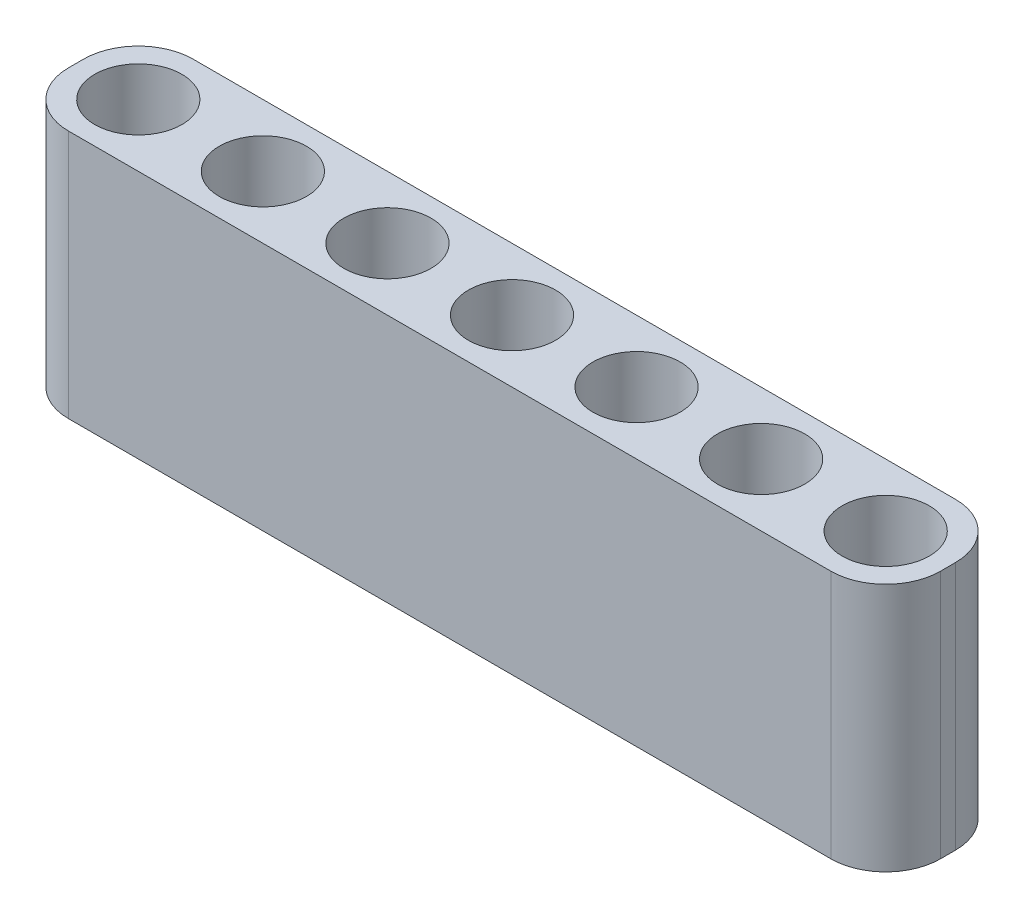
SolidWorks part; units mm, degrees
ref_plane "Front Plane" through (0, 0, 0) normal (0, 0, 1) x (1, 0, 0)
ref_plane "Top Plane" through (0, 0, 0) normal (0, 1, 0) x (1, 0, 0)
ref_plane "Right Plane" through (0, 0, 0) normal (1, 0, 0) x (0, 0, -1)
sketch "Sketch1" plane through (0, 0, 0) normal (0, 1, 0) x (1, 0, 0)
  line L1 (2.2, 0) -> (32.8, 0)
  line L2 (0, 2.2) -> (0, 2.8)
  line L3 (2.2, 5) -> (32.8, 5)
  line L4 (35, 2.2) -> (35, 2.8)
  circle A0 centre (2.5, 2.5) radius 1.75
  circle A2 centre (7.5, 2.5) radius 1.75
  circle A3 centre (12.5, 2.5) radius 1.75
  circle A4 centre (17.5, 2.5) radius 1.75
  circle A5 centre (22.5, 2.5) radius 1.75
  circle A6 centre (27.5, 2.5) radius 1.75
  circle A7 centre (32.5, 2.5) radius 1.75
  arc A8 (32.8, 5) -> (35, 2.8) centre (32.8, 2.8) cw
  arc A9 (32.8, 0) -> (35, 2.2) centre (32.8, 2.2) ccw
  arc A10 (0, 2.8) -> (2.2, 5) centre (2.2, 2.8) cw
  arc A11 (2.2, 0) -> (0, 2.2) centre (2.2, 2.2) cw
  point P21 (35, 5)
  point P26 (0, 5)
  point P29 (0, 0)
  dimension "D3" = 3.5
  dimension "D4" = 2.5
  dimension "D5" = 7
  dimension "D6" = 2.5
  dimension "D7" = 2.2
  dimension "D1" = 35
  dimension "D2" = 5
extrude "Boss-Extrude1" add sketch "Sketch1" along normal blind 10
